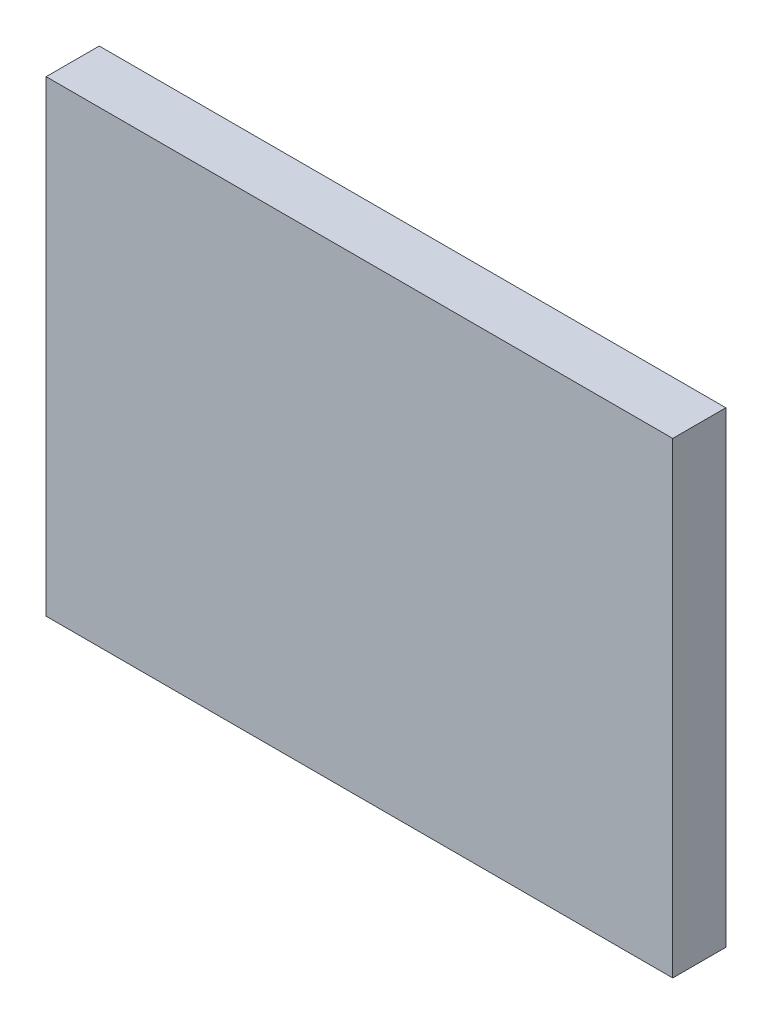
SolidWorks part; units mm, degrees
ref_plane "Plano frontal" through (0, 0, 0) normal (0, 0, 1) x (1, 0, 0)
ref_plane "Plano superior" through (0, 0, 0) normal (0, 1, 0) x (1, 0, 0)
ref_plane "Plano direito" through (0, 0, 0) normal (1, 0, 0) x (0, 0, -1)
sketch "Esboço1" plane through (0, 0, 0) normal (0, 0, 1) x (1, 0, 0)
  line L1 (29.5, -22) -> (-29.5, -22)
  line L2 (29.5, -22) -> (29.5, 22)
  line L3 (29.5, 22) -> (-29.5, 22)
  line L4 (-29.5, -22) -> (-29.5, 22)
  line L5 (29.5, -22) -> (-29.5, 22) construction
  line L6 (29.5, 22) -> (-29.5, -22) construction
  point P0 (0, 0)
  dimension "D1" = 59
  dimension "D2" = 44
extrude "Ressalto-extrusão1" add sketch "Esboço1" along normal blind 5
